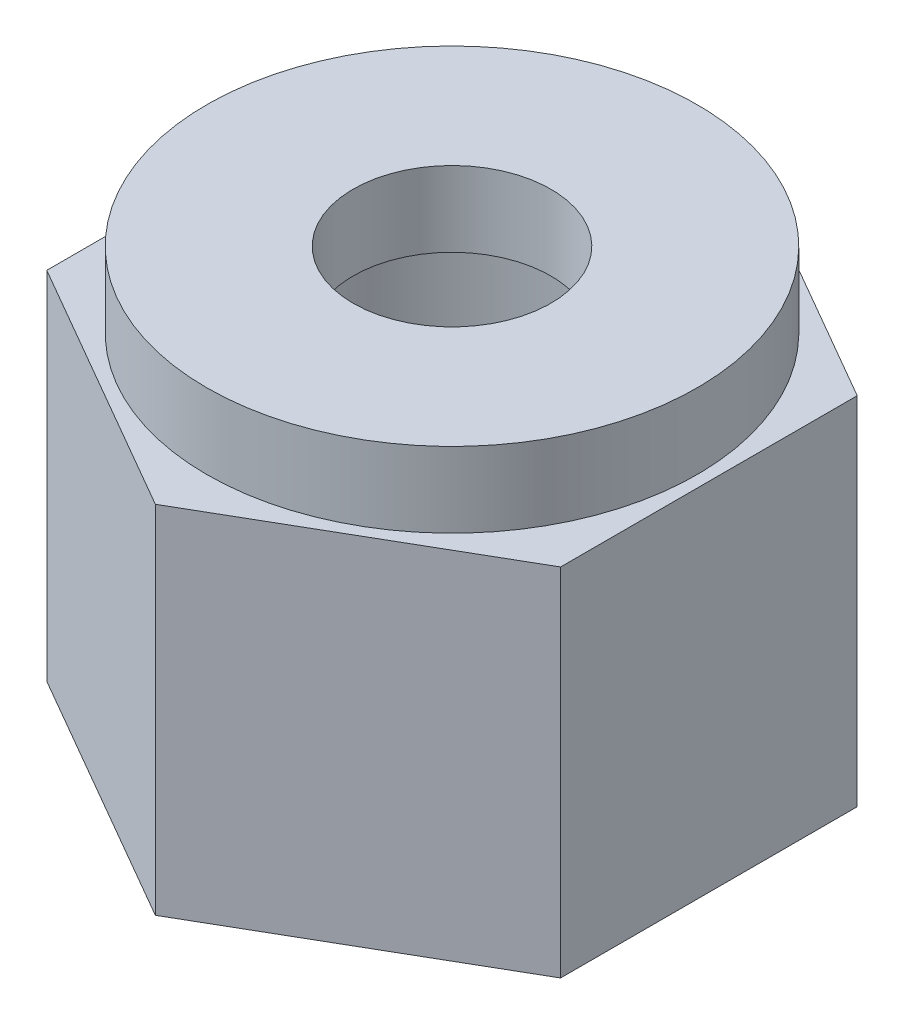
SolidWorks part; units mm, degrees
ref_plane "Спереди" through (0, 0, 0) normal (0, 0, 1) x (1, 0, 0)
ref_plane "Сверху" through (0, 0, 0) normal (0, 1, 0) x (1, 0, 0)
ref_plane "Справа" through (0, 0, 0) normal (1, 0, 0) x (0, 0, -1)
sketch "Эскиз1" plane through (0, 0, 0) normal (0, 1, 0) x (1, 0, 0)
  line L1 (0, 15) -> (-12.9904, 7.5)
  line L2 (-12.9904, 7.5) -> (-12.9904, -7.5)
  line L3 (-12.9904, -7.5) -> (0, -15)
  line L4 (0, -15) -> (12.9904, -7.5)
  line L5 (12.9904, -7.5) -> (12.9904, 7.5)
  line L6 (12.9904, 7.5) -> (0, 15)
  circle A0 centre (0, 0) radius 12.9904 construction
  dimension "D1" = 15
ref_plane "Плоскость1" through (0, -18, 0) normal (0, 1, 0) x (1, 0, 0)
sketch "Эскиз2" plane through (0, -18, 0) normal (0, 1, 0) x (1, 0, 0)
  line L0 (-12.9904, -7.5) -> (0, -15) construction
  line L1 (0, -15) -> (12.9904, -7.5) construction
  line L2 (12.9904, -7.5) -> (12.9904, 7.5) construction
  line L3 (12.9904, 7.5) -> (0, 15) construction
  line L4 (0, 15) -> (-12.9904, 7.5) construction
  line L5 (-12.9904, 7.5) -> (-12.9904, -7.5) construction
  line L6 (-12.9904, -7.5) -> (0, -15)
  line L7 (0, -15) -> (12.9904, -7.5)
  line L8 (12.9904, -7.5) -> (12.9904, 7.5)
  line L9 (12.9904, 7.5) -> (0, 15)
  line L10 (0, 15) -> (-12.9904, 7.5)
  line L11 (-12.9904, 7.5) -> (-12.9904, -7.5)
loft "По сечениям1" add profiles "Эскиз2", "Эскиз1"
sketch "Эскиз3" plane through (0, -18, 0) normal (0, -1, 0) x (1, 0, 0)
  circle A0 centre (0, 0) radius 10.188
  dimension "D1" = 20.376
extrude "Вырез-Вытянуть1" cut sketch "Эскиз3" against normal through all
cosmetic thread "Условное изображение резьбы1" parameters "D2"=22
sketch "Эскиз4" plane through (0, 0, 0) normal (0, 1, 0) x (1, 0, 0)
  circle A0 centre (0, 0) radius 12.4
  dimension "D1" = 24.8
ref_plane "Плоскость2" through (0, 3.8, 0) normal (0, 1, 0) x (1, 0, 0)
sketch "Эскиз5" plane through (0, 3.8, 0) normal (0, 1, 0) x (1, 0, 0)
  circle A0 centre (0, 0) radius 12.4 construction
  circle A1 centre (0, 0) radius 12.4
loft "По сечениям2" add profiles "Эскиз5", "Эскиз4"
sketch "Эскиз6" plane through (0, 3.8, 0) normal (0, 1, 0) x (1, 0, 0)
  circle A0 centre (0, 0) radius 5
  dimension "D1" = 10
extrude "Вырез-Вытянуть2" cut sketch "Эскиз6" against normal through all
